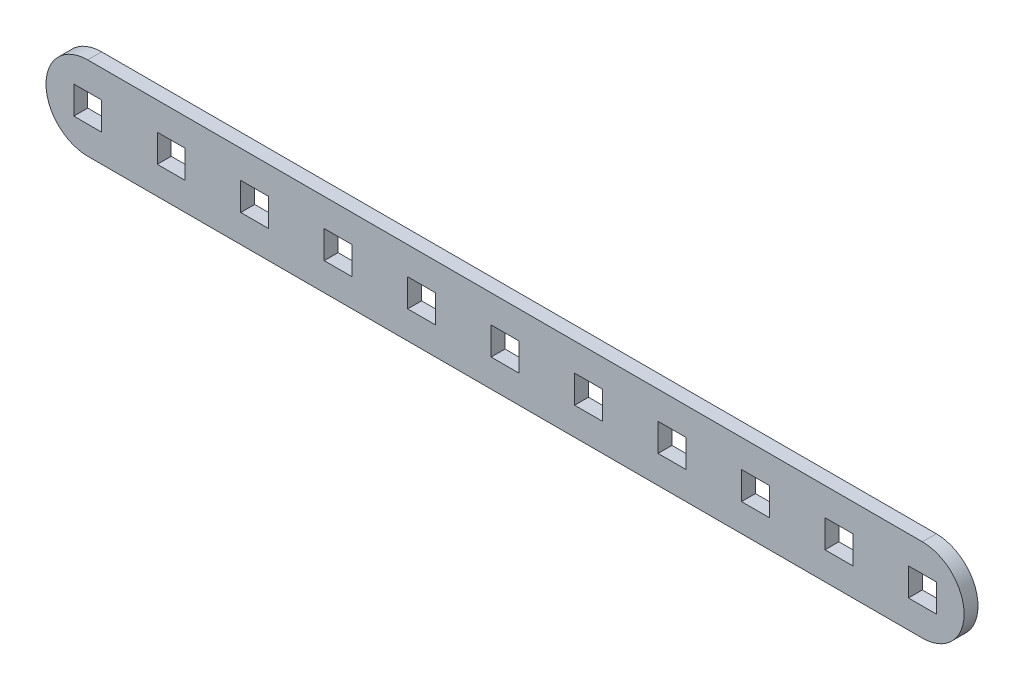
SolidWorks part; units mm, degrees
ref_plane "Alzado" through (0, 0, 0) normal (0, 0, 1) x (1, 0, 0)
ref_plane "Planta" through (0, 0, 0) normal (0, 1, 0) x (1, 0, 0)
ref_plane "Vista lateral" through (0, 0, 0) normal (1, 0, 0) x (0, 0, -1)
sketch "Model" plane through (0, 0, 0) normal (0, 0, 1) x (1, 0, 0)
  line L0 (8.4048, 293.775) -> (8.4048, 290.775)
  line L1 (11.4048, 293.775) -> (8.4048, 293.775)
  line L2 (11.4048, 290.775) -> (11.4048, 293.775)
  line L3 (8.4048, 290.775) -> (11.4048, 290.775)
  line L4 (17.4048, 293.775) -> (17.4048, 290.775)
  line L5 (20.4048, 293.775) -> (17.4048, 293.775)
  line L6 (20.4048, 290.775) -> (20.4048, 293.775)
  line L7 (17.4048, 290.775) -> (20.4048, 290.775)
  line L8 (26.4048, 293.775) -> (26.4048, 290.775)
  line L9 (29.4048, 293.775) -> (26.4048, 293.775)
  line L10 (29.4048, 290.775) -> (29.4048, 293.775)
  line L11 (26.4048, 290.775) -> (29.4048, 290.775)
  line L12 (35.4048, 293.775) -> (35.4048, 290.775)
  line L13 (38.4048, 293.775) -> (35.4048, 293.775)
  line L14 (38.4048, 290.775) -> (38.4048, 293.775)
  line L15 (35.4048, 290.775) -> (38.4048, 290.775)
  line L16 (44.4048, 293.775) -> (44.4048, 290.775)
  line L17 (47.4048, 293.775) -> (44.4048, 293.775)
  line L18 (47.4048, 290.775) -> (47.4048, 293.775)
  line L19 (44.4048, 290.775) -> (47.4048, 290.775)
  line L20 (53.4048, 293.775) -> (53.4048, 290.775)
  line L21 (56.4048, 293.775) -> (53.4048, 293.775)
  line L22 (56.4048, 290.775) -> (56.4048, 293.775)
  line L23 (53.4048, 290.775) -> (56.4048, 290.775)
  line L24 (62.4048, 293.775) -> (62.4048, 290.775)
  line L25 (65.4048, 293.775) -> (62.4048, 293.775)
  line L26 (65.4048, 290.775) -> (65.4048, 293.775)
  line L27 (62.4048, 290.775) -> (65.4048, 290.775)
  line L28 (71.4048, 293.775) -> (71.4048, 290.775)
  line L29 (74.4048, 293.775) -> (71.4048, 293.775)
  line L30 (74.4048, 290.775) -> (74.4048, 293.775)
  line L31 (71.4048, 290.775) -> (74.4048, 290.775)
  line L32 (80.4048, 293.775) -> (80.4048, 290.775)
  line L33 (83.4048, 293.775) -> (80.4048, 293.775)
  line L34 (83.4048, 290.775) -> (83.4048, 293.775)
  line L35 (80.4048, 290.775) -> (83.4048, 290.775)
  line L36 (89.4048, 293.775) -> (89.4048, 290.775)
  line L37 (92.4048, 293.775) -> (89.4048, 293.775)
  line L38 (92.4048, 290.775) -> (92.4048, 293.775)
  line L39 (89.4048, 290.775) -> (92.4048, 290.775)
  line L40 (98.4048, 293.775) -> (98.4048, 290.775)
  line L41 (101.4048, 293.775) -> (98.4048, 293.775)
  line L42 (101.4048, 290.775) -> (101.4048, 293.775)
  line L43 (98.4048, 290.775) -> (101.4048, 290.775)
  line L44 (9.9048, 296.775) -> (99.9048, 296.775)
  line L45 (9.9048, 287.775) -> (99.9048, 287.775)
  arc A0 (9.9048, 296.775) -> (9.9048, 287.775) centre (9.9048, 292.275) ccw
  arc A1 (99.9048, 287.775) -> (99.9048, 296.775) centre (99.9048, 292.275) ccw
extrude "Saliente-Extruir1" add sketch "Model" along normal blind 1.5
